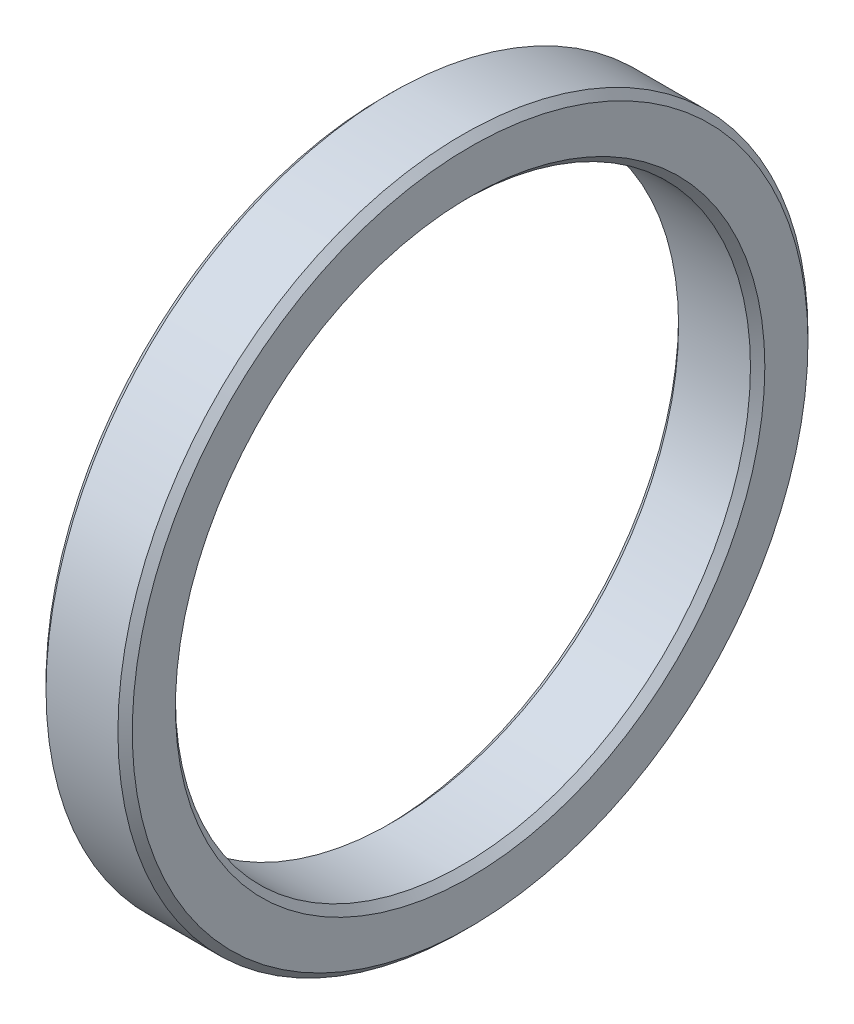
SolidWorks part; units mm, degrees
ref_plane "前视基准面" through (0, 0, 0) normal (0, 0, 1) x (1, 0, 0)
ref_plane "上视基准面" through (0, 0, 0) normal (0, 1, 0) x (1, 0, 0)
ref_plane "右视基准面" through (0, 0, 0) normal (1, 0, 0) x (0, 0, -1)
other "Configuration Table"
sketch "草图1" plane through (0, 0, 0) normal (1, 0, 0) x (0, 0, -1)
  circle A0 centre (0, 0) radius 24
  circle A1 centre (0, 0) radius 20
  dimension "D1" = 40
  dimension "D2" = 48
extrude "凸台-拉伸1" add sketch "草图1" along normal blind 6
chamfer "倒角1" distance 0.5 angle 45 4 edges at (0, 0, -24) (6, 0, -24) (0, 0, -20) (6, 0, -20)
